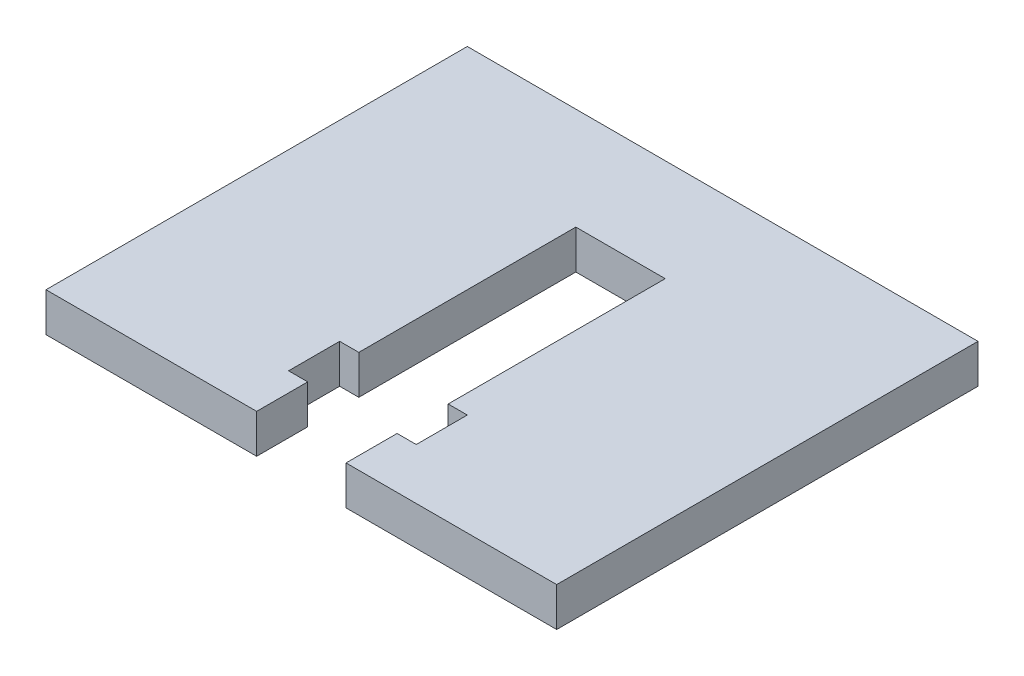
SolidWorks part; units mm, degrees
ref_plane "Front Plane" through (0, 0, 0) normal (0, 0, 1) x (1, 0, 0)
ref_plane "Top Plane" through (0, 0, 0) normal (0, 1, 0) x (1, 0, 0)
ref_plane "Right Plane" through (0, 0, 0) normal (1, 0, 0) x (0, 0, -1)
sketch "Sketch1" plane through (0, 0, 0) normal (0, 1, 0) x (1, 0, 0)
  line L0 (0, 0) -> (0, 33)
  line L1 (0, 33) -> (40, 33)
  line L2 (40, 33) -> (40, 0)
  line L3 (40, 0) -> (23.5, 0)
  line L4 (23.5, 0) -> (23.5, 4)
  line L5 (23.5, 4) -> (25, 4)
  line L6 (25, 4) -> (25, 8)
  line L7 (25, 8) -> (23.5, 8)
  line L8 (23.5, 8) -> (23.5, 25)
  line L9 (23.5, 25) -> (16.5, 25)
  line L10 (16.5, 25) -> (16.5, 8)
  line L11 (16.5, 8) -> (15, 8)
  line L12 (15, 8) -> (15, 4)
  line L13 (15, 4) -> (16.5, 4)
  line L14 (16.5, 4) -> (16.5, 0)
  line L15 (16.5, 0) -> (0, 0)
  dimension "D1" = 33
  dimension "D2" = 16.5
  dimension "D3" = 16.5
  dimension "D4" = 40
  dimension "D5" = 1.5
  dimension "D6" = 4
  dimension "D7" = 1.5
  dimension "D8" = 4
  dimension "D9" = 17
  dimension "D10" = 17
  dimension "D11" = 1.5
  dimension "D12" = 4
  dimension "D13" = 1.5
extrude "Boss-Extrude1" add sketch "Sketch1" along normal blind 3.05
